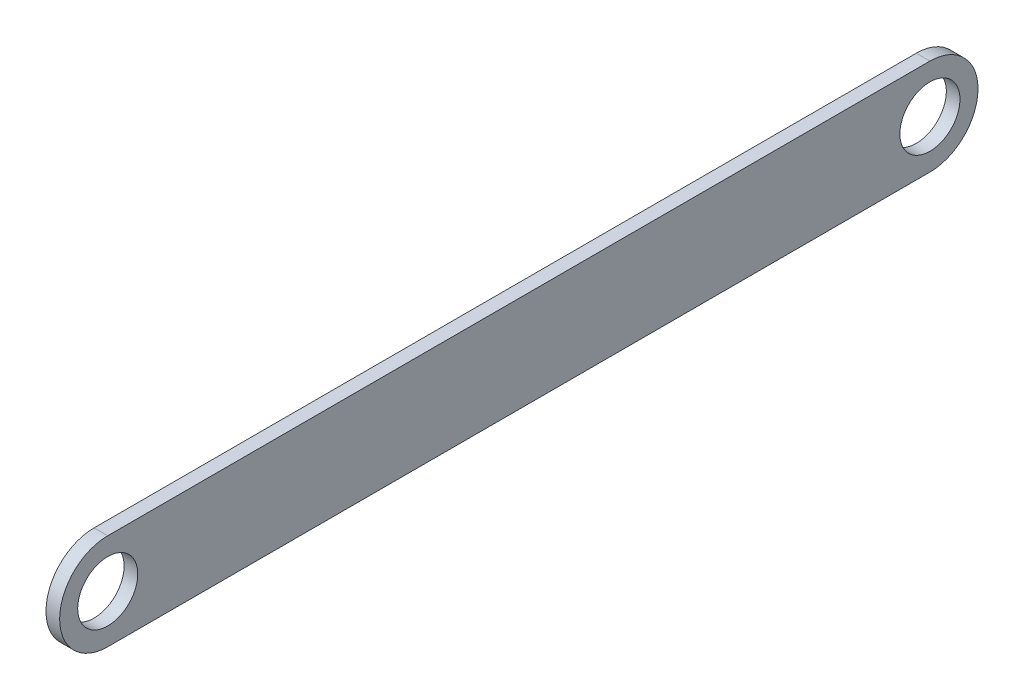
SolidWorks part; units mm, degrees
ref_plane "Front Plane" through (0, 0, 0) normal (0, 0, 1) x (1, 0, 0)
ref_plane "Top Plane" through (0, 0, 0) normal (0, 1, 0) x (1, 0, 0)
ref_plane "Right Plane" through (0, 0, 0) normal (1, 0, 0) x (0, 0, -1)
sketch "Sketch1" plane through (0, 0, 0) normal (1, 0, 0) x (0, 0, -1)
  line L0 (0, 0) -> (1737.36, 0) construction
  line L1 (0, 101.6) -> (1737.36, 101.6)
  line L2 (0, -101.6) -> (1737.36, -101.6)
  arc A0 (0, 101.6) -> (0, -101.6) centre (0, 0) ccw
  arc A1 (1737.36, -101.6) -> (1737.36, 101.6) centre (1737.36, 0) ccw
  circle A2 centre (0, 0) radius 63.5
  circle A3 centre (1737.36, 0) radius 63.5
  point P2 (868.68, 0)
  dimension "D2" = 101.6
  dimension "D3" = 127
  dimension "D4" = 127
  dimension "D1" = 1737.36
extrude "Boss-Extrude1" add sketch "Sketch1" along normal blind 28.829
